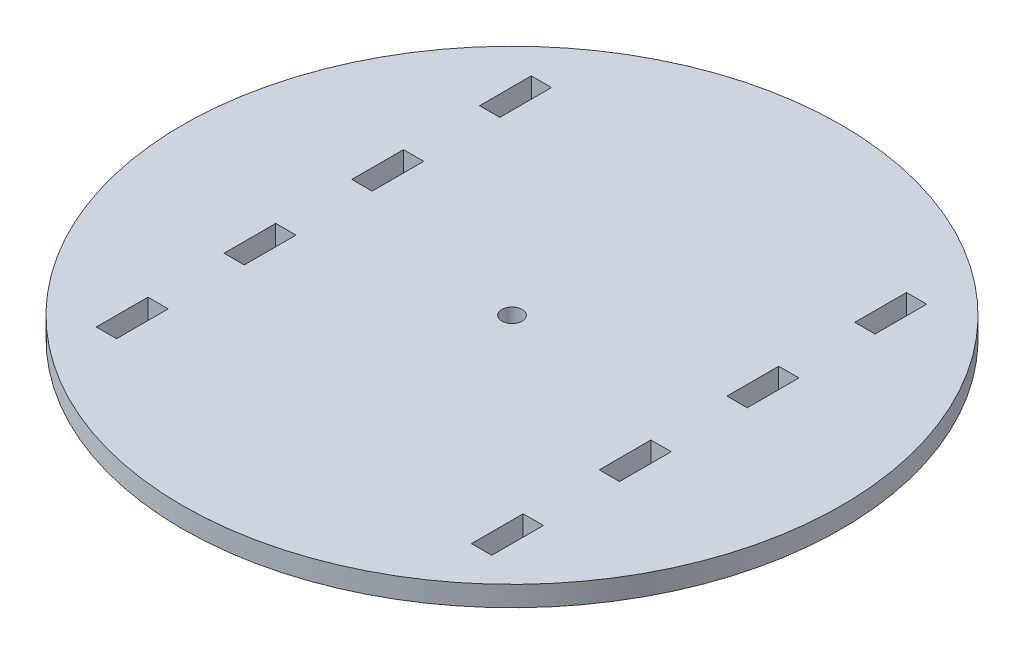
SolidWorks part; units mm, degrees
ref_plane "Alzado" through (0, 0, 0) normal (0, 0, 1) x (1, 0, 0)
ref_plane "Planta" through (0, 0, 0) normal (0, 1, 0) x (1, 0, 0)
ref_plane "Vista lateral" through (0, 0, 0) normal (1, 0, 0) x (0, 0, -1)
sketch "Croquis2" plane through (0, 0, 0) normal (0, 1, 0) x (1, 0, 0)
  line L0 (-39, 17.6) -> (-35, 17.6)
  line L1 (-39, 42.8) -> (-35, 42.8)
  line L2 (-39, 42.8) -> (-39, 32.6)
  line L3 (-39, 32.6) -> (-35, 32.6)
  line L4 (-35, 42.8) -> (-35, 32.6)
  line L5 (-39, 17.6) -> (-39, 7.4)
  line L6 (-39, 7.4) -> (-35, 7.4)
  line L7 (-35, 17.6) -> (-35, 7.4)
  line L8 (-39, -32.8) -> (-35, -32.8)
  line L9 (-39, -32.8) -> (-39, -43)
  line L10 (-39, -43) -> (-35, -43)
  line L11 (-35, -32.8) -> (-35, -43)
  line L12 (-39, -7.6) -> (-35, -7.6)
  line L13 (-39, -7.6) -> (-39, -17.8)
  line L14 (-39, -17.8) -> (-35, -17.8)
  line L15 (-35, -7.6) -> (-35, -17.8)
  line L16 (0, 0) -> (-65, 0) construction
  line L17 (0, 0) -> (0, 23.1076) construction
  line L18 (35, -32.8) -> (35, -43)
  line L19 (39, -32.8) -> (39, -43)
  line L20 (39, -43) -> (35, -43)
  line L21 (39, -32.8) -> (35, -32.8)
  line L22 (39, -17.8) -> (35, -17.8)
  line L23 (39, -7.6) -> (39, -17.8)
  line L24 (35, -7.6) -> (35, -17.8)
  line L25 (39, -7.6) -> (35, -7.6)
  line L26 (39, 7.4) -> (35, 7.4)
  line L27 (35, 42.8) -> (35, 32.6)
  line L28 (35, 17.6) -> (35, 7.4)
  line L29 (39, 17.6) -> (35, 17.6)
  line L30 (39, 17.6) -> (39, 7.4)
  line L31 (39, 32.6) -> (35, 32.6)
  line L32 (39, 42.8) -> (35, 42.8)
  line L33 (39, 42.8) -> (39, 32.6)
  circle A0 centre (0, 0) radius 65
  point P19 (-35, 12.5)
  point P22 (-37, 17.6)
  point P23 (-37, -7.6)
  dimension "D1" = 130
  dimension "D2" = 4
  dimension "D3" = 10.2
  dimension "D4" = 15
  dimension "D5" = 15
  dimension "D6" = 15
  dimension "D7" = 35
  dimension "D8" = 7.6
extrude "Saliente-Extruir1" add sketch "Croquis2" along normal blind 4 contours A0
sketch "Croquis3" plane through (0, 4, 0) normal (0, 1, 0) x (1, 0, 0)
  line L8 (-39, 7.4) -> (-35, 7.4)
  line L9 (-35, 7.4) -> (-35, 17.6)
  line L10 (-35, 17.6) -> (-39, 17.6)
  line L11 (-39, 17.6) -> (-39, 7.4)
  line L12 (-39, -7.6) -> (-35, -7.6)
  line L13 (-35, -7.6) -> (-35, -17.8)
  line L14 (-35, -17.8) -> (-39, -17.8)
  line L15 (-39, -17.8) -> (-39, -7.6)
  line L16 (-39, -32.8) -> (-35, -32.8)
  line L17 (-35, -32.8) -> (-35, -43)
  line L18 (-35, -43) -> (-39, -43)
  line L19 (-39, -43) -> (-39, -32.8)
  line L20 (-39, 42.8) -> (-35, 42.8)
  line L21 (-35, 42.8) -> (-35, 32.6)
  line L22 (-35, 32.6) -> (-39, 32.6)
  line L23 (-39, 32.6) -> (-39, 42.8)
  line L24 (0, 0) -> (0, 15.2849) construction
  line L25 (0, 0) -> (0, 23.1076) construction
  line L26 (35, 32.6) -> (39, 32.6)
  line L27 (35, 42.8) -> (35, 32.6)
  line L28 (39, 42.8) -> (35, 42.8)
  line L29 (39, 32.6) -> (39, 42.8)
  line L30 (35, 17.6) -> (39, 17.6)
  line L31 (35, 7.4) -> (35, 17.6)
  line L32 (39, 7.4) -> (35, 7.4)
  line L33 (39, 17.6) -> (39, 7.4)
  line L34 (35, -17.8) -> (39, -17.8)
  line L35 (35, -7.6) -> (35, -17.8)
  line L36 (39, -7.6) -> (35, -7.6)
  line L37 (39, -17.8) -> (39, -7.6)
  line L38 (35, -43) -> (39, -43)
  line L39 (35, -32.8) -> (35, -43)
  line L40 (39, -32.8) -> (35, -32.8)
  line L41 (39, -43) -> (39, -32.8)
  point P53 (0, 0)
extrude "Cortar-Extruir6" cut sketch "Croquis3" against normal up to next
sketch "Croquis4" plane through (0, 4, 0) normal (0, 1, 0) x (1, 0, 0)
  circle A0 centre (0, 0) radius 2
  dimension "D1" = 4
extrude "Cortar-Extruir7" cut sketch "Croquis4" against normal blind 10
